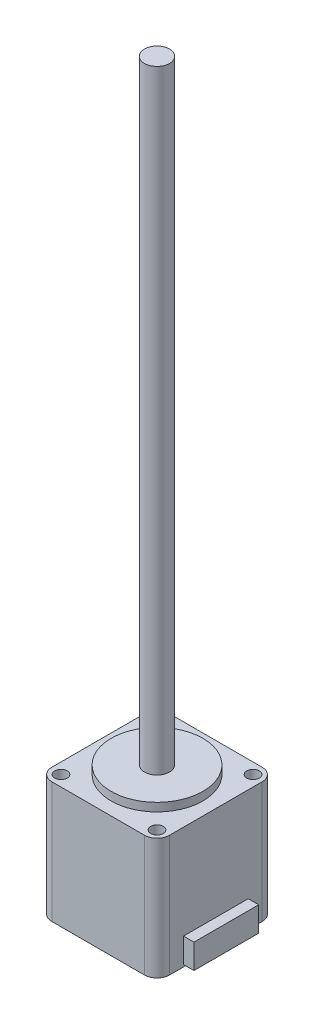
SolidWorks part; units mm, degrees
ref_plane "Front Plane" through (0, 0, 0) normal (0, 0, 1) x (1, 0, 0)
ref_plane "Top Plane" through (0, 0, 0) normal (0, 1, 0) x (1, 0, 0)
ref_plane "Right Plane" through (0, 0, 0) normal (1, 0, 0) x (0, 0, -1)
ref_axis "Axis1" through (0, -54.2812, 0) along (0, 1, 0)
sketch "Sketch2" plane through (0, 0, 0) normal (1, 0, 0) x (0, 0, -1)
  line L0 (11, 2) -> (0, 2) construction
  line L1 (0, 2) -> (-11, 2)
  line L2 (-11, 2) -> (-11, 0)
  line L3 (-11, 0) -> (0, 0)
  line L5 (0, 0) -> (0, 2)
  point P2 (0, 0)
  point P6 (0, 0)
  dimension "D1" = 22
  dimension "D2" = 2
revolve "Revolve2" add sketch "Sketch2" angle 360 about axis through (0, -54.2812, 0) along (0, 1, 0)
sketch "Sketch1" plane through (0, 0, 0) normal (1, 0, 0) x (0, 0, -1)
  line L0 (0, 2) -> (-3, 2)
  line L1 (-3, 2) -> (-3, 149)
  line L2 (-3, 149) -> (0, 149)
  line L3 (0, -54.2812) -> (0, 159.9098) construction
  line L4 (0, 149) -> (0, 2)
  line L5 (0, 2) -> (3, 2) construction
  line L6 (3, 2) -> (3, 149) construction
  line L7 (3, 149) -> (0, 149) construction
  line L8 (11, 2) -> (-11, 2) construction
  dimension "D1" = 147
  dimension "D2" = 6
sketch "Sketch3" plane through (0, 0, 0) normal (1, 0, 0) x (0, 0, -1)
  line L0 (-14.1, 0) -> (14.1, 0)
  line L1 (14.1, 0) -> (14.1, -29)
  line L2 (14.1, -29) -> (-14.1, -29)
  line L3 (-14.1, -29) -> (-14.1, 0)
  line L4 (0, -54.2812) -> (0, 159.9098) construction
  line L5 (-11, 0) -> (11, 0) construction
  point P3 (0, 0)
  dimension "D1" = 29
  dimension "D2" = 28.2
extrude "Boss-Extrude1" add sketch "Sketch3" along normal mid plane 28.2
fillet "Fillet1" radius 3 4 edges at (-14.1, -14.5, -14.1) (14.1, -14.5, -14.1) (14.1, -14.5, 14.1) (-14.1, -14.5, 14.1)
sketch "Sketch5" plane through (14.1, 0, 0) normal (1, 0, 0) x (0, 0, -1)
  line L0 (0, -54.2812) -> (0, 159.9098) construction
  line L1 (-7.75, -28.5) -> (7.75, -28.5)
  line L2 (-7.75, -28.5) -> (-7.75, -22.6)
  line L3 (-7.75, -22.6) -> (7.75, -22.6)
  line L4 (7.75, -28.5) -> (7.75, -22.6)
  line L5 (-7.75, -28.5) -> (-7.75, -29) construction
  line L6 (-11.1, -29) -> (11.1, -29) construction
  point P4 (0, -22.6)
  point P8 (0, 0)
  dimension "D1" = 0.5
  dimension "D2" = 15.5
  dimension "D3" = 5.9
extrude "Boss-Extrude2" add sketch "Sketch5" along normal blind 2.5
revolve "Revolve3" add sketch "Sketch1" angle 360 about axis through (0, -54.2812, 0) along (0, 1, 0)
sketch "Sketch7" plane through (0, 0, 0) normal (0, 1, 0) x (1, 0, 0)
  line L1 (11.5, -11.5) -> (-11.5, -11.5) construction
  line L2 (11.5, -11.5) -> (11.5, 11.5) construction
  line L3 (11.5, 11.5) -> (-11.5, 11.5) construction
  line L4 (-11.5, -11.5) -> (-11.5, 11.5) construction
  line L5 (11.5, -11.5) -> (-11.5, 11.5) construction
  line L6 (11.5, 11.5) -> (-11.5, -11.5) construction
  circle A0 centre (-11.5, 11.5) radius 1.5
  circle A1 centre (-11.5, -11.5) radius 1.5
  circle A2 centre (11.5, -11.5) radius 1.5
  circle A3 centre (11.5, 11.5) radius 1.5
  point P0 (0, 0)
  dimension "D2" = 3
  dimension "D1" = 23
extrude "Cut-Extrude1" cut sketch "Sketch7" against normal up to next
